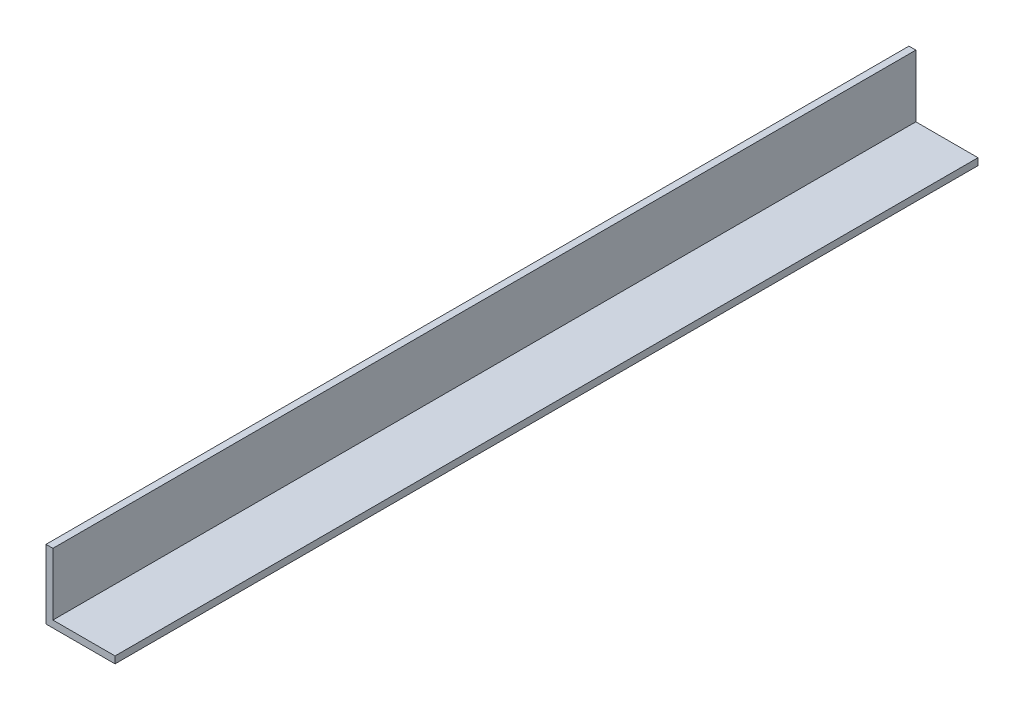
SolidWorks part; units mm, degrees
ref_plane "Спереди" through (0, 0, 0) normal (0, 0, 1) x (1, 0, 0)
ref_plane "Сверху" through (0, 0, 0) normal (0, 1, 0) x (1, 0, 0)
ref_plane "Справа" through (0, 0, 0) normal (1, 0, 0) x (0, 0, -1)
sketch "Эскиз1" plane through (0, 0, 0) normal (0, 0, 1) x (1, 0, 0)
  line L0 (0, 0) -> (0, 40)
  line L1 (0, 40) -> (4, 40)
  line L2 (4, 40) -> (4, 4)
  line L3 (4, 4) -> (40, 4)
  line L4 (40, 4) -> (40, 0)
  line L5 (40, 0) -> (0, 0)
  dimension "D1" = 40
  dimension "D2" = 40
  dimension "D3" = 4
  dimension "D4" = 4
extrude "Бобышка-Вытянуть1" add sketch "Эскиз1" along normal blind 500
